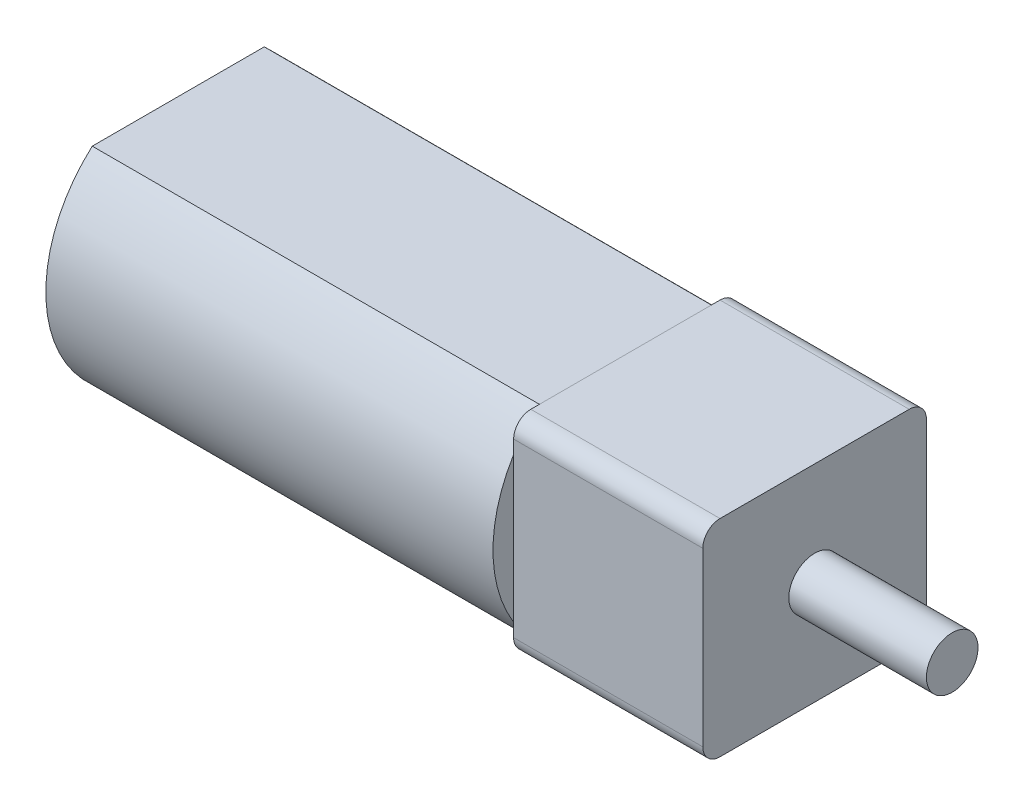
SolidWorks part; units mm, degrees
ref_plane "Спереди" through (0, 0, 0) normal (0, 0, 1) x (1, 0, 0)
ref_plane "Сверху" through (0, 0, 0) normal (0, 1, 0) x (1, 0, 0)
ref_plane "Справа" through (0, 0, 0) normal (1, 0, 0) x (0, 0, -1)
sketch "Эскиз1" plane through (0, 0, 0) normal (1, 0, 0) x (0, 0, -1)
  line L0 (2.7, 12) -> (12.7, 12)
  line L1 (0, 0) -> (15.4, 0) construction
  line L2 (0, 0) -> (0, 12) construction
  line L3 (0, 12) -> (15.4, 12) construction
  line L4 (15.4, 0) -> (15.4, 12) construction
  line L5 (0, 6) -> (15.4, 6) construction
  line L6 (7.7, 12) -> (7.7, 0) construction
  line L7 (2.7, 0) -> (12.7, 0)
  arc A0 (2.7, 12) -> (2.7, 0) centre (8.0167, 6) ccw
  arc A1 (12.7, 12) -> (12.7, 0) centre (7.3833, 6) cw
  point P7 (7.7, 12)
  point P8 (7.7, 12)
  dimension "D1" = 15.4
  dimension "D2" = 12
  dimension "D3" = 10
extrude "Бобышка-Вытянуть1" add sketch "Эскиз1" along normal blind 26
sketch "Эскиз2" plane through (26, 0, 0) normal (1, 0, 0) x (0, 0, -1)
  line L0 (2.7, 12) -> (12.7, 0) construction
  line L2 (1.2, 0) -> (14.2, 0)
  line L3 (1.2, 0) -> (1.2, 12)
  line L4 (1.2, 12) -> (14.2, 12)
  line L5 (14.2, 0) -> (14.2, 12)
  line L6 (1.2, 0) -> (14.2, 12) construction
  line L7 (1.2, 12) -> (14.2, 0) construction
  point P4 (7.7, 6)
  dimension "D1" = 13
  dimension "D2" = 12
extrude "Бобышка-Вытянуть2" add sketch "Эскиз2" along normal blind 11 separate body
sketch "Эскиз3" plane through (37, 0, 0) normal (1, 0, 0) x (0, 0, -1)
  line L0 (1.2, 12) -> (14.2, 0) construction
  circle A0 centre (7.7, 6) radius 1.5
  dimension "D1" = 3
extrude "Бобышка-Вытянуть3" add sketch "Эскиз3" along normal blind 8
sketch "Эскиз4" plane through (0, 0, 0) normal (-1, 0, 0) x (0, 0, 1)
  line L0 (-12.7, 12) -> (-2.7, 0) construction
  circle A0 centre (-7.7, 6) radius 2.5
  dimension "D1" = 5
extrude "Бобышка-Вытянуть4" add sketch "Эскиз4" along normal blind 2
fillet "Скругление1" radius 0.5 1 edges at (-2, 6, -5.2)
fillet "Скругление2" radius 1 4 edges at (31.5, 0, -1.2) (31.5, 0, -14.2) (31.5, 12, -14.2) (31.5, 12, -1.2)
